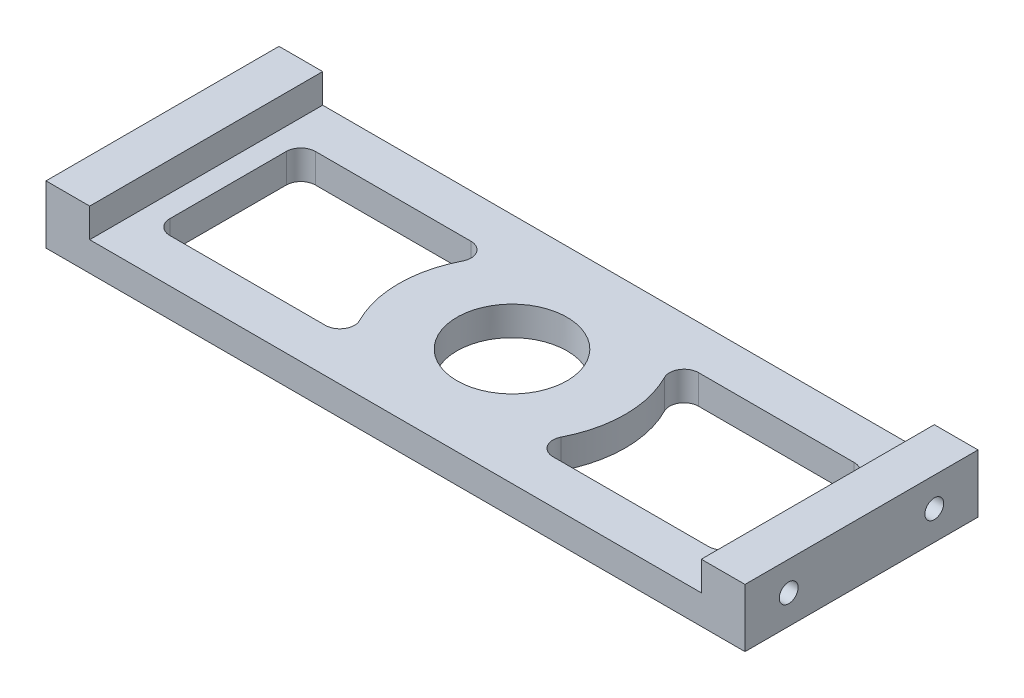
SolidWorks part; units mm, degrees
material "6061 Alloy"
ref_plane "Front" through (0, 0, 0) normal (0, 0, 1) x (1, 0, 0)
ref_plane "Top" through (0, 0, 0) normal (0, 1, 0) x (1, 0, 0)
ref_plane "Right" through (0, 0, 0) normal (1, 0, 0) x (0, 0, -1)
sketch "Sketch1" plane through (0, 0, 0) normal (0, 1, 0) x (1, 0, 0)
  line L1 (-38.1, -12.7) -> (38.1, -12.7)
  line L2 (-38.1, -12.7) -> (-38.1, 12.7)
  line L3 (-38.1, 12.7) -> (38.1, 12.7)
  line L4 (38.1, -12.7) -> (38.1, 12.7)
  line L5 (-38.1, -12.7) -> (38.1, 12.7) construction
  line L6 (-38.1, 12.7) -> (38.1, -12.7) construction
  point P0 (0, 0)
  dimension "D1" = 25.4
  dimension "D2" = 76.2
extrude "Boss-Extrude1" add sketch "Sketch1" along normal mid plane 3.175 contours L3 L4 L1 L2
sketch "Sketch2" plane through (0, 1.5875, 0) normal (0, 1, 0) x (1, 0, 0)
  point P0 (0, 0)
hole_wizard "Ø12.0mm Dowel Hole1" positions "Sketch3" profile "Sketch4" hole size "Ø12.0" standard "ANSI Metric" end condition up to next
sketch "Sketch3" plane through (0, 1.5875, 0) normal (0, 1, 0) x (1, 0, 0)
  point P0 (0, 0)
sketch "Sketch4" plane through (0, 1.5875, 0) normal (1, 0, 0) x (0, 0, 1)
  line L0 (0, 0) -> (0, 3.175)
  line L1 (0, 3.175) -> (6, 3.175)
  line L2 (6, 3.175) -> (6, 0)
  line L5 (6, 0) -> (0, 0)
  line L11 (0, -6.35) -> (0, 107.95) construction
  dimension "Thru Hole Dia." = 12
  dimension "Thru Hole Depth" = 3.175
sketch "Sketch5" plane through (0, 1.5875, 0) normal (0, 1, 0) x (1, 0, 0)
  line L0 (-38.1, -12.7) -> (38.1, -12.7) construction
  line L1 (-38.1, 12.7) -> (-33.3375, 12.7)
  line L2 (-38.1, 12.7) -> (-38.1, -12.7)
  line L3 (-38.1, -12.7) -> (-33.3375, -12.7)
  line L4 (-33.3375, 12.7) -> (-33.3375, -12.7)
  dimension "D1" = 4.7625
extrude "Boss-Extrude2" add sketch "Sketch5" along normal blind 3.175
mirror "Mirror1" about plane through (0, 0, 0) normal (1, 0, 0) of "Boss-Extrude2"
hole_wizard "M2.5x0.45 Tapped Hole1" positions "Sketch7" profile "Sketch9" tap size "M2.5x0.45" standard "ANSI Metric"
sketch "Sketch7" plane through (-38.1, 0, 0) normal (-1, 0, 0) x (0, 0, 1)
  point P6 (7.9375, 1.5875)
  point P9 (-7.9375, 1.5875)
sketch "Sketch9" plane through (-38.1, 1.5875, 7.9375) normal (0, 1, 0) x (0, 0, 1)
  line L0 (0, 0) -> (0, 4.6159)
  line L1 (0, 4.6159) -> (1.025, 4)
  line L2 (1.025, 4) -> (1.025, 0)
  line L5 (1.025, 0) -> (0, 0)
  line L10 (0, 4.6159) -> (-1.025, 4) construction
  line L11 (0, -6.35) -> (0, 107.95) construction
  dimension "Tap Drill Dia." = 2.05
  dimension "Tap Drill Depth" = 4
  dimension "Drill Angle" = 118
cosmetic thread "Hole Thread1" parameters "D1"=5.08, "D2"=2.5
cosmetic thread "Hole Thread2" parameters "D1"=5.08, "D2"=2.5
hole_wizard "M2.5x0.45 Tapped Hole2" positions "Sketch10" profile "Sketch11" tap size "M2.5x0.45" standard "ANSI Metric"
sketch "Sketch10" plane through (38.1, 0, 0) normal (1, 0, 0) x (0, 0, -1)
  point P13 (-7.9375, 1.5875)
  point P16 (7.9375, 1.5875)
sketch "Sketch11" plane through (38.1, 1.5875, 7.9375) normal (0, 1, 0) x (0, 0, -1)
  line L0 (0, 0) -> (0, 4.6159)
  line L1 (0, 4.6159) -> (1.025, 4)
  line L2 (1.025, 4) -> (1.025, 0)
  line L5 (1.025, 0) -> (0, 0)
  line L10 (0, 4.6159) -> (-1.025, 4) construction
  line L11 (0, -6.35) -> (0, 107.95) construction
  dimension "Tap Drill Dia." = 2.05
  dimension "Tap Drill Depth" = 4
  dimension "Drill Angle" = 118
cosmetic thread "Hole Thread3" parameters "D1"=5.08, "D2"=2.5
cosmetic thread "Hole Thread4" parameters "D1"=5.08, "D2"=2.5
sketch "Sketch12" plane through (0, 1.5875, 0) normal (0, 1, 0) x (1, 0, 0)
  line L0 (-30.9562, 7.9375) -> (-30.9562, -7.9375)
  line L1 (-30.9562, -7.9375) -> (-9.4614, -7.9375)
  line L2 (-30.9562, 7.9375) -> (-9.4614, 7.9375)
  line L3 (-50, 0) -> (50, 0) construction
  line L5 (-33.3375, 12.7) -> (33.3375, 12.7) construction
  line L6 (-33.3375, 12.7) -> (-38.1, 12.7) construction
  arc A0 (-9.4614, 7.9375) -> (-9.4614, -7.9375) centre (0, 0) ccw
  circle A1 centre (0, 0) radius 6 construction
  point P5 (-30.9562, 0)
  point P11 (-35.7188, 12.7)
  dimension "D3" = 6.35
  dimension "D1" = 4.7625
  dimension "D2" = 4.7625
extrude "Cut-Extrude1" cut sketch "Sketch12" against normal through all
mirror "Mirror2" about plane through (0, 0, 0) normal (1, 0, 0) of "Cut-Extrude1"
fillet "Fillet1" radius 1.5875 8 edges at (30.9562, 0, 7.9375) (30.9562, 0, -7.9375) (9.4614, 0, -7.9375) (9.4614, 0, 7.9375) (-30.9562, 0, 7.9375) (-30.9562, 0, -7.9375) (-9.4614, 0, -7.9375) (-9.4614, 0, 7.9375)
